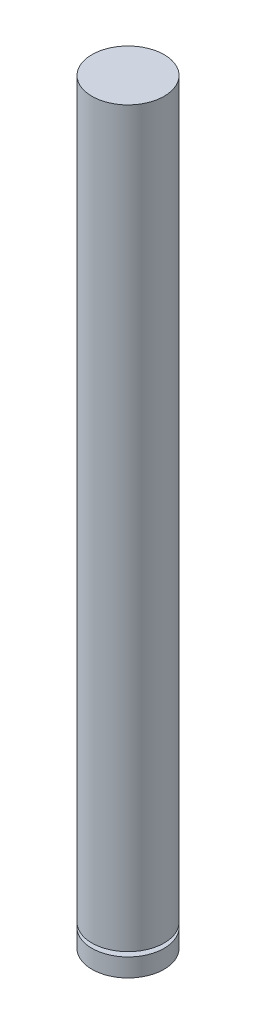
SolidWorks part; units mm, degrees
ref_plane "Front Plane" through (0, 0, 0) normal (0, 0, 1) x (1, 0, 0)
ref_plane "Top Plane" through (0, 0, 0) normal (0, 1, 0) x (1, 0, 0)
ref_plane "Right Plane" through (0, 0, 0) normal (1, 0, 0) x (0, 0, -1)
sketch "Sketch1" plane through (0, 0, 0) normal (0, 1, 0) x (1, 0, 0)
  circle A0 centre (0, 0) radius 1.585
  dimension "D1" = 3.17
extrude "Boss-Extrude1" add sketch "Sketch1" along normal blind 33.2
sketch "Sketch2" plane through (0, 0, 0) normal (0, 0, 1) x (1, 0, 0)
  line L0 (-1.585, 0) -> (-1.585, 33.2)
  line L1 (1.585, 33.2) -> (1.585, 0)
  line L2 (1.585, 33.2) -> (1.585, 0)
  line L3 (-1.585, 0) -> (-1.585, 33.2)
  line L4 (-1.585, 0) -> (1.585, 0) construction
  line L5 (1.585, 0.8) -> (1.085, 0.8)
  line L6 (1.585, 0.8) -> (1.585, 1)
  line L7 (1.585, 1) -> (1.085, 1)
  line L8 (1.085, 0.8) -> (1.085, 1)
  dimension "D1" = 0.2
  dimension "D2" = 0.5
  dimension "D3" = 0.8
ref_axis "Axis1" through (0, -1.7, 0) along (0, 1, 0)
revolve "Cut-Revolve1" cut sketch "Sketch2" angle 360 about axis through (0, -1.7, 0) along (0, 1, 0)
